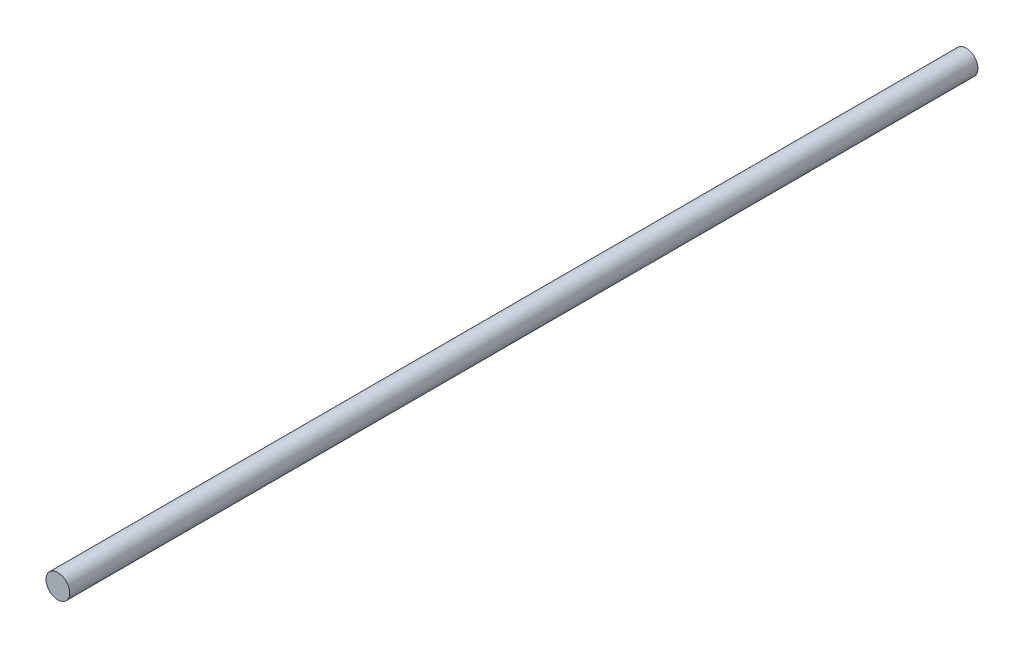
SolidWorks part; units mm, degrees
ref_plane "Front Plane" through (0, 0, 0) normal (0, 0, 1) x (1, 0, 0)
ref_plane "Top Plane" through (0, 0, 0) normal (0, 1, 0) x (1, 0, 0)
ref_plane "Right Plane" through (0, 0, 0) normal (1, 0, 0) x (0, 0, -1)
sketch "Sketch1" plane through (0, 0, 0) normal (0, 0, 1) x (1, 0, 0)
  circle A0 centre (0, 0) radius 15
  dimension "D1" = 30
extrude "Boss-Extrude1" add sketch "Sketch1" along normal blind 1150
